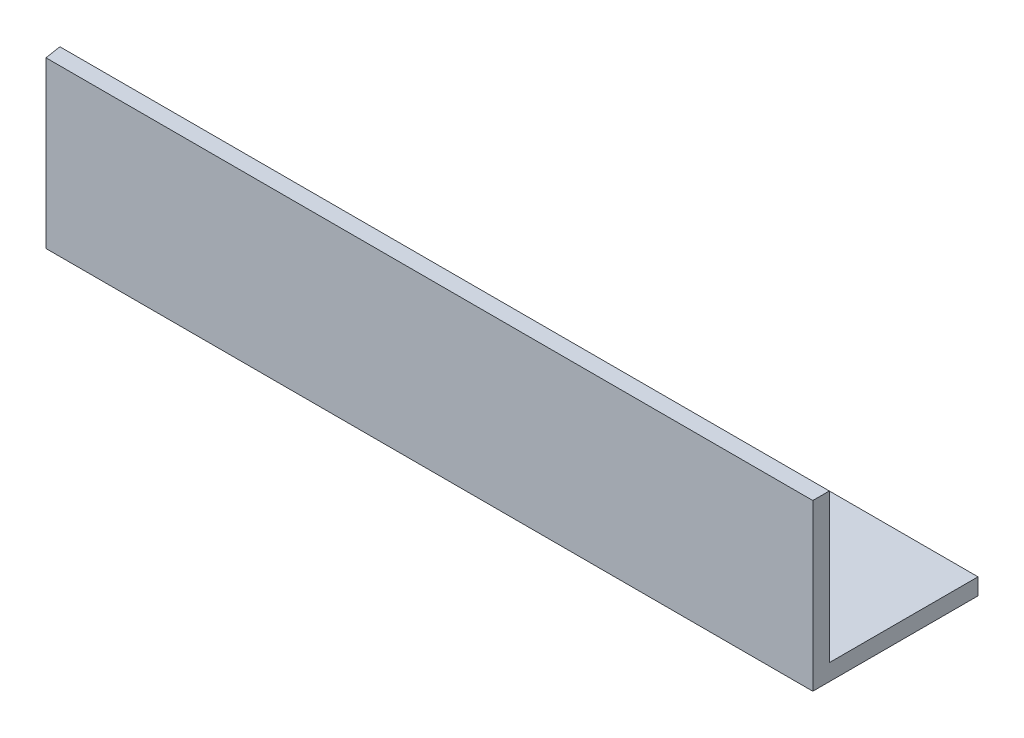
SolidWorks part; units mm, degrees
ref_plane "Front Plane" through (0, 0, 0) normal (0, 0, 1) x (1, 0, 0)
ref_plane "Top Plane" through (0, 0, 0) normal (0, 1, 0) x (1, 0, 0)
ref_plane "Right Plane" through (0, 0, 0) normal (1, 0, 0) x (0, 0, -1)
sketch "Sketch1" plane through (0, 0, 0) normal (1, 0, 0) x (0, 0, -1)
  line L0 (0, 20) -> (0, 0)
  line L1 (0, 0) -> (20, 0)
  line L2 (20, 0) -> (20, 2)
  line L3 (20, 2) -> (2, 2)
  line L4 (2, 2) -> (2, 20)
  line L5 (0, 20) -> (2, 20)
  dimension "D1" = 20
  dimension "D2" = 20
  dimension "D3" = 2
  dimension "D4" = 2
extrude "Boss-Extrude1" add sketch "Sketch1" along normal blind 96
sketch "Sketch2" plane through (0, 0, 0) normal (0, 1, 0) x (1, 0, 0)
  line L7 (0, 20) -> (0, 0)
  line L8 (0, 20) -> (3.1677, 0)
  line L9 (96, 0) -> (0, 0) construction
  line L10 (3.1677, 0) -> (0, 0)
  dimension "D1" = 9
extrude "Cut-Extrude1" cut sketch "Sketch2" along normal through all
